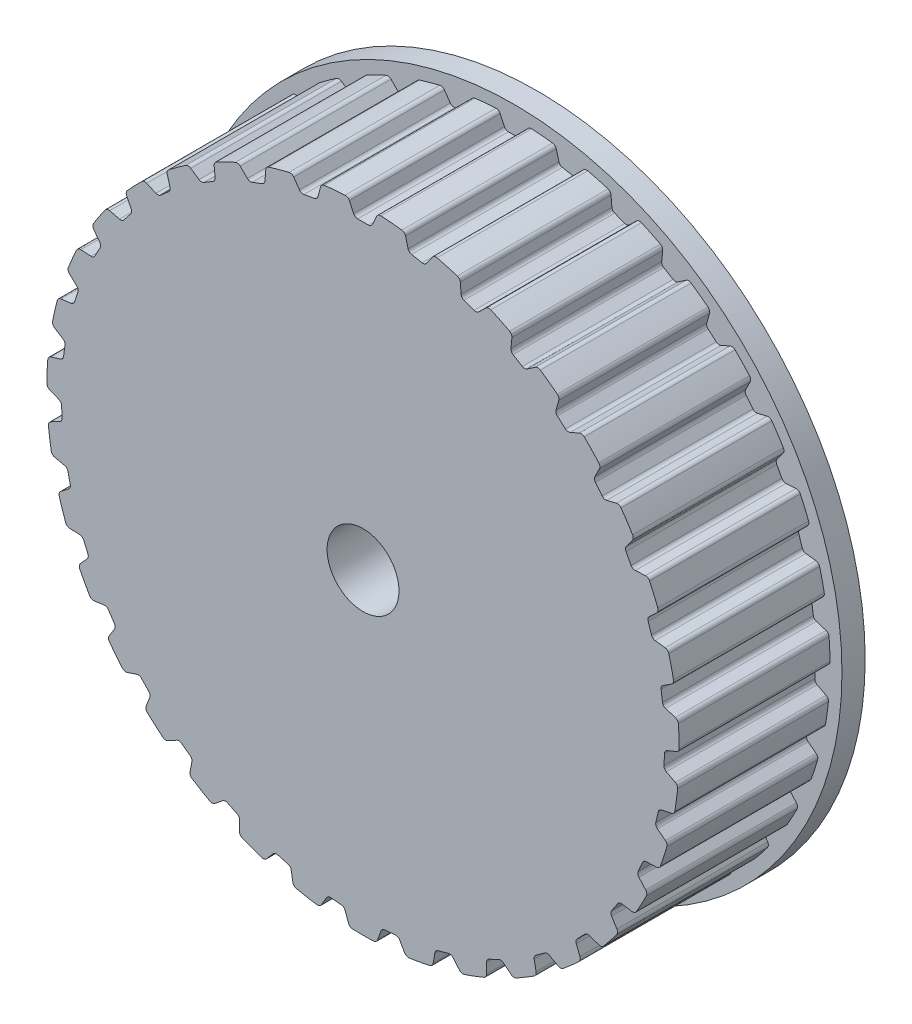
SolidWorks part; units mm, degrees
ref_plane "Front Plane" through (0, 0, 0) normal (0, 0, 1) x (1, 0, 0)
ref_plane "Top Plane" through (0, 0, 0) normal (0, 1, 0) x (1, 0, 0)
ref_plane "Right Plane" through (0, 0, 0) normal (1, 0, 0) x (0, 0, -1)
sketch "Sketch1" plane through (0, 0, 0) normal (0, 0, 1) x (1, 0, 0)
  line L0 (0, 0) -> (-77.4679, 0) construction
  circle A0 centre (0, 0) radius 28.2977
  dimension "D1" = 56.5955
extrude "Boss-Extrude1" add sketch "Sketch1" along normal blind 13 and the other way blind 2
sketch "Sketch2" plane through (0, 0, 13) normal (0, 0, 1) x (1, 0, 0)
  line L4 (0, -36.7733) -> (0, 127.7263) construction
  line L5 (0.4648, 25.9977) -> (-0.4648, 25.9977)
  line L6 (-0.8092, 26.2172) -> (-1.1767, 27.0053)
  line L8 (-2.5366, 28.1838) -> (-2.4443, 27.158)
  line L9 (2.5366, 28.1838) -> (2.4443, 27.158)
  line L10 (0.8092, 26.2172) -> (1.1767, 27.0053)
  circle A0 centre (0, 0) radius 28.2977 construction
  arc A1 (-1.5426, 27.2241) -> (-2.4443, 27.158) centre (0, 0) ccw
  arc A3 (-0.4648, 25.9977) -> (-0.8092, 26.2172) centre (-0.4648, 26.3777) cw
  arc A4 (-1.1767, 27.0053) -> (-1.5426, 27.2241) centre (-1.5211, 26.8447) ccw
  arc A5 (1.5426, 27.2241) -> (2.4443, 27.158) centre (0, 0) cw
  arc A6 (1.1767, 27.0053) -> (1.5426, 27.2241) centre (1.5211, 26.8447) cw
  arc A7 (0.4648, 25.9977) -> (0.8092, 26.2172) centre (0.4648, 26.3777) ccw
  arc A8 (2.5366, 28.1838) -> (-2.5366, 28.1838) centre (0, 0) ccw
  point P9 (0, 28.2977)
  point P16 (-1.285, 27.2375)
  point P24 (0, 25.9977)
  dimension "D1" = 54.5355
  dimension "D6" = 0.38
  dimension "D7" = 0.38
  dimension "D2" = 25
  dimension "D3" = 2.57
  dimension "D5" = 2.3
  dimension "D4" = 5.08
extrude "Cut-Extrude1" cut sketch "Sketch2" against normal blind 13
pattern_circular "CirPattern2" count 35 over 360 about axis through (0, 0, 0) along (0, 0, 1) of "Cut-Extrude1"
sketch "Sketch6" plane through (0, 0, 13) normal (0, 0, 1) x (1, 0, 0)
  circle A0 centre (0, 0) radius 3.1
  dimension "D1" = 6.2
extrude "Cut-Extrude2" cut sketch "Sketch6" against normal through all both and the other way through all
equation "\"n\" = 35'Number of teeth"
equation "\"t\"= 5.08mm'Tooth pitch"
equation "\"beta\" = 25deg'Tooth angle"
equation "\"ht\"= 1.27mm'Tooth height"
equation "\"rr\"= 0.38mm'Foot radius"
equation "\"ra\"= 0.38mm'Head radius"
equation "\"s\"= 2.57mm'Tooth width"
equation "\"hs\"= 2.3mm'Overall belt thickness"
equation "\"do\"= \"n\" * \"t\" / PI'Outer diameter"
equation "\"di\" = \"do\" - 2 * ( \"hs\" - \"ht\" )'Inner diameter"
equation "\"D1@Sketch1\"=\"do\""
equation "\"D1@Sketch2\"=\"di\""
equation "\"D2@Sketch2\"=\"beta\""
equation "\"D3@Sketch2\"=\"s\""
equation "\"D6@Sketch2\"=\"ra\""
equation "\"D7@Sketch2\"=\"rr\""
equation "\"b1\" = 13mm'Thickness of pulley"
equation "\"b2\"= 2mm'Thickness of cover"
equation "\"D1@Boss-Extrude1\"=\"b1\""
equation "\"D4@Sketch2\"=\"t\""
equation "\"D5@Sketch2\"=\"hs\""
equation "\"D1@CirPattern2\"=\"n\""
equation "\"D2@Boss-Extrude1\"=\"b2\""
equation "\"borepulley\"= 6.2mm"
equation "\"D1@Sketch6\"=\"borepulley\""
equation "\"D1@Cut-Extrude1\"=\"b1\""
